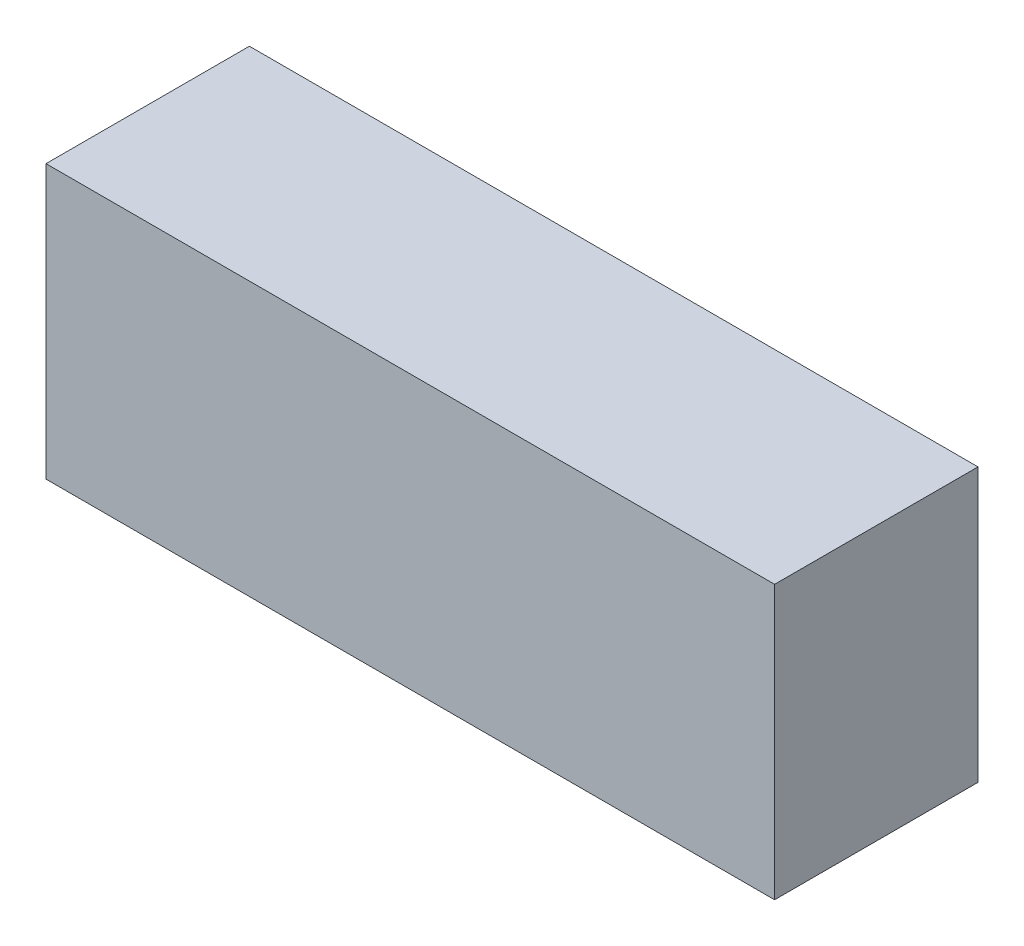
SolidWorks part; units mm, degrees
ref_plane "Plano frontal" through (0, 0, 0) normal (0, 0, 1) x (1, 0, 0)
ref_plane "Plano superior" through (0, 0, 0) normal (0, 1, 0) x (1, 0, 0)
ref_plane "Plano direito" through (0, 0, 0) normal (1, 0, 0) x (0, 0, -1)
sketch "Esboço1" plane through (0, 0, 0) normal (0, 0, 1) x (1, 0, 0)
  line L1 (60, -22.5) -> (-60, -22.5)
  line L2 (60, -22.5) -> (60, 22.5)
  line L3 (60, 22.5) -> (-60, 22.5)
  line L4 (-60, -22.5) -> (-60, 22.5)
  line L5 (60, -22.5) -> (-60, 22.5) construction
  line L6 (60, 22.5) -> (-60, -22.5) construction
  point P0 (0, 0)
  dimension "D1" = 120
  dimension "D2" = 45
extrude "Ressalto-extrusão1" add sketch "Esboço1" against normal blind 33.5
sketch "Esboço2" plane through (0, 0, 0) normal (0, 0, 1) x (1, 0, 0)
  line L0 (-60, -22.5) -> (60, 22.5) construction
  line L1 (-60, 22.5) -> (60, -22.5) construction
  line L4 (-60, 22.5) -> (-60, -22.5)
  line L5 (-60, -22.5) -> (60, -22.5)
  line L6 (60, -22.5) -> (60, 22.5)
  line L7 (60, 22.5) -> (-60, 22.5)
  line L8 (-60, 22.5) -> (-60, -22.5) construction
  line L9 (-60, -22.5) -> (60, -22.5) construction
  line L10 (60, -22.5) -> (60, 22.5) construction
  line L11 (60, 22.5) -> (-60, 22.5) construction
  dimension "D1" = 0
